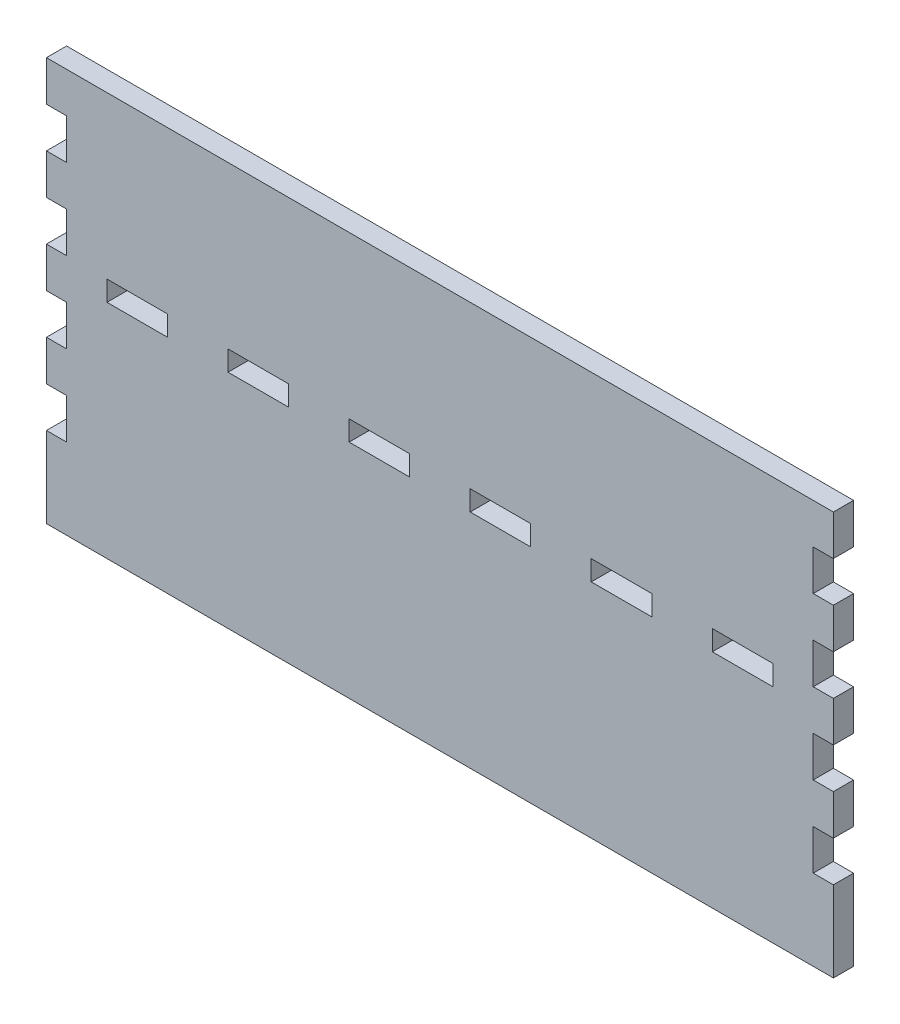
SolidWorks part; units mm, degrees
material "Pin"
ref_plane "Front" through (0, 0, 0) normal (0, 0, 1) x (1, 0, 0)
ref_plane "Top" through (0, 0, 0) normal (0, 1, 0) x (1, 0, 0)
ref_plane "Right" through (0, 0, 0) normal (1, 0, 0) x (0, 0, -1)
sketch "Esquisse1" plane through (0, 0, 0) normal (0, 0, 1) x (1, 0, 0)
  line L1 (-123.825, 63.5) -> (123.825, 63.5)
  line L2 (-123.825, 63.5) -> (-123.825, -63.5)
  line L3 (-123.825, -63.5) -> (123.825, -63.5)
  line L4 (123.825, 63.5) -> (123.825, -63.5)
  line L5 (-123.825, 63.5) -> (123.825, -63.5) construction
  line L6 (-123.825, -63.5) -> (123.825, 63.5) construction
  point P0 (0, 0)
  dimension "D1" = 127
  dimension "D2" = 247.65
extrude "Boss.-Extru.1" add sketch "Esquisse1" along normal blind 6.35
sketch "Esquisse2" plane through (0, 0, 6.35) normal (0, 0, 1) x (1, 0, 0)
  line L0 (-123.825, 63.5) -> (-123.825, -63.5) construction
  line L1 (-104.775, 12.7) -> (-85.725, 12.7)
  line L2 (-104.775, 12.7) -> (-104.775, 6.35)
  line L3 (-104.775, 6.35) -> (-85.725, 6.35)
  line L4 (-85.725, 12.7) -> (-85.725, 6.35)
  line L5 (123.825, 63.5) -> (-123.825, 63.5) construction
  dimension "D1" = 6.35
  dimension "D2" = 19.05
  dimension "D3" = 19.05
  dimension "D4" = 50.8
extrude "Enlèv. mat.-Extru.1" cut sketch "Esquisse2" against normal blind 6.35
pattern_linear "Répétition linéaire1" count 6 spacing 38.1 along (1, 0, 0) count 2 spacing 57.15 along (0, -1, 0) of "Enlèv. mat.-Extru.1"
sketch "Esquisse3" plane through (0, 0, 6.35) normal (0, 0, 1) x (1, 0, 0)
  line L0 (-123.825, 63.5) -> (-123.825, -63.5) construction
  line L1 (-123.825, 50.8) -> (-117.475, 50.8)
  line L2 (-123.825, 50.8) -> (-123.825, 38.1)
  line L3 (-123.825, 38.1) -> (-117.475, 38.1)
  line L4 (-117.475, 50.8) -> (-117.475, 38.1)
  line L5 (123.825, 63.5) -> (-123.825, 63.5) construction
  dimension "D1" = 12.7
  dimension "D2" = 12.7
  dimension "D3" = 6.35
extrude "Enlèv. mat.-Extru.2" cut sketch "Esquisse3" against normal blind 6.35
pattern_linear "Répétition linéaire2" count 4 spacing 25.4 along (0, -1, 0) count 2 spacing 241.3 along (1, 0, 0) of "Enlèv. mat.-Extru.2"
